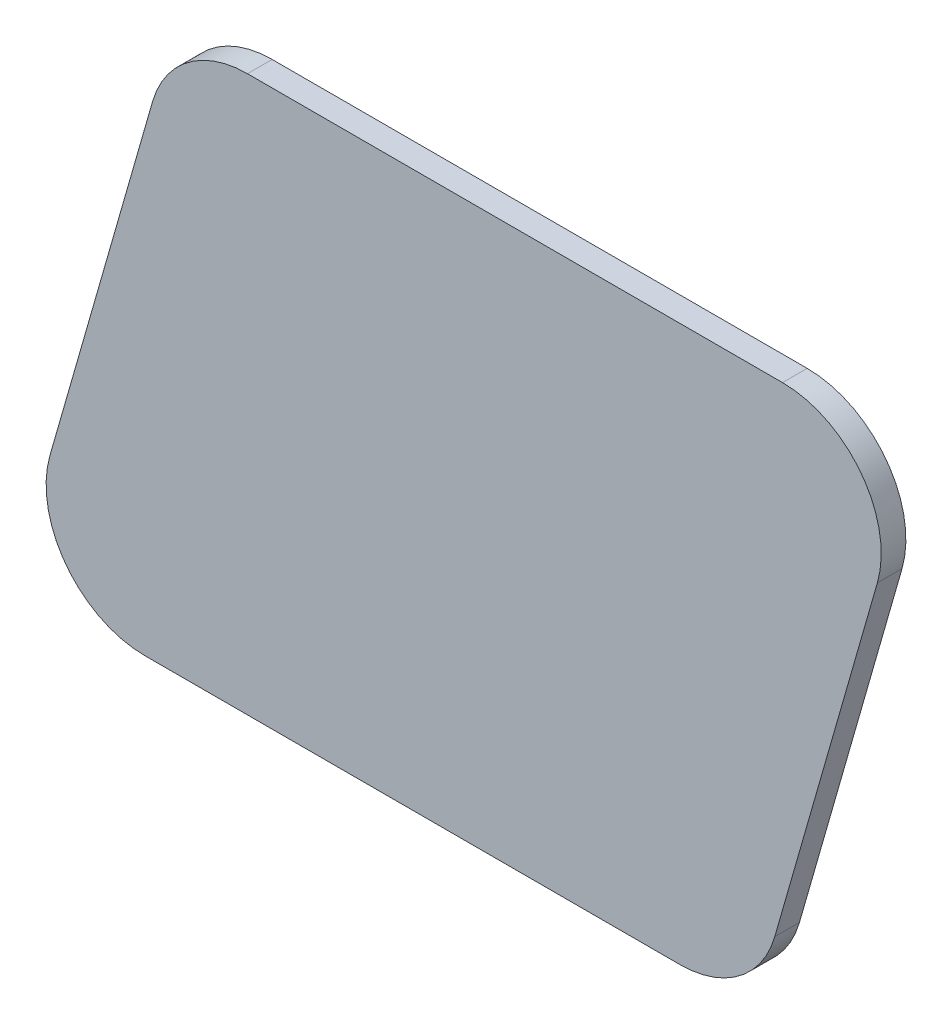
SolidWorks part; units mm, degrees
material "ABS PC"
ref_plane "Front Plane" through (0, 0, 0) normal (0, 0, 1) x (1, 0, 0)
ref_plane "Top Plane" through (0, 0, 0) normal (0, 1, 0) x (1, 0, 0)
ref_plane "Right Plane" through (0, 0, 0) normal (1, 0, 0) x (0, 0, -1)
sketch "Sketch1" plane through (0, 0, 0) normal (0, 0, 1) x (1, 0, 0)
  line L0 (10.6173, 0) -> (53.9721, 0)
  line L1 (2.9274, 10.2057) -> (11.2456, 39.2057)
  line L2 (61.662, 5.7943) -> (69.9802, 34.7943)
  line L3 (18.9355, 45) -> (62.2903, 45)
  line L4 (0, 0) -> (0, 15) construction
  line L5 (0, 15) -> (52.9412, 15) construction
  line L6 (0, 0) -> (9.9832, 0) construction
  line L7 (9.9832, 0) -> (9.9832, 15) construction
  arc A0 (2.9274, 10.2057) -> (10.6173, 0) centre (10.6173, 8) ccw
  arc A1 (61.662, 5.7943) -> (53.9721, 0) centre (53.9721, 8) cw
  arc A2 (62.2903, 45) -> (69.9802, 34.7943) centre (62.2903, 37) cw
  arc A3 (18.9355, 45) -> (11.2456, 39.2057) centre (18.9355, 37) ccw
  point P14 (60, 0)
  dimension "D4" = 8
  dimension "D1" = 60
  dimension "D2" = 45
  dimension "D3" = 15
extrude "Boss-Extrude1" add sketch "Sketch1" along normal blind 2
